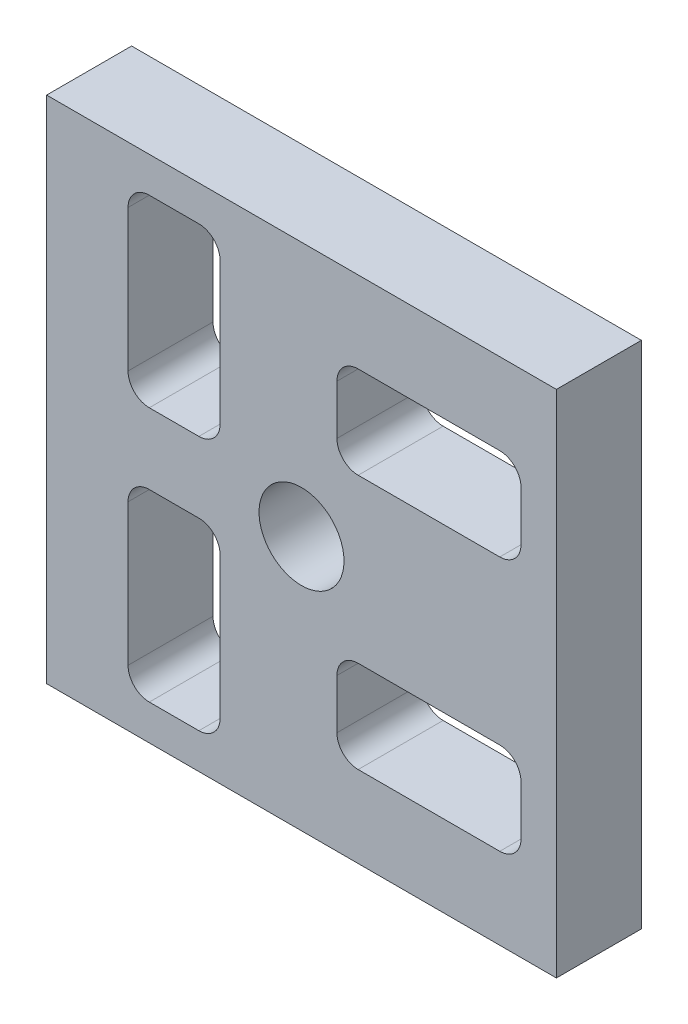
SolidWorks part; units mm, degrees
ref_plane "Alzado" through (0, 0, 0) normal (0, 0, 1) x (1, 0, 0)
ref_plane "Planta" through (0, 0, 0) normal (0, 1, 0) x (1, 0, 0)
ref_plane "Vista lateral" through (0, 0, 0) normal (1, 0, 0) x (0, 0, -1)
sketch "Model" plane through (0, 0, 0) normal (0, 0, 1) x (1, 0, 0)
  line L0 (208.8359, 161.3332) -> (208.8359, 179.3332)
  line L1 (190.8359, 179.3332) -> (190.8359, 161.3332)
  line L2 (201.8359, 176.4582) -> (206.8359, 176.4582)
  line L3 (207.5859, 175.7082) -> (207.5859, 173.9582)
  line L4 (206.8359, 173.2082) -> (201.8359, 173.2082)
  line L5 (201.0859, 173.9582) -> (201.0859, 175.7082)
  line L6 (201.8359, 167.4582) -> (206.8359, 167.4582)
  line L7 (207.5859, 166.7082) -> (207.5859, 164.9582)
  line L8 (206.8359, 164.2082) -> (201.8359, 164.2082)
  line L9 (201.0859, 164.9582) -> (201.0859, 166.7082)
  line L10 (196.9609, 168.3332) -> (196.9609, 163.3332)
  line L11 (196.2109, 162.5832) -> (194.4609, 162.5832)
  line L12 (193.7109, 163.3332) -> (193.7109, 168.3332)
  line L13 (194.4609, 169.0832) -> (196.2109, 169.0832)
  line L14 (196.9609, 177.3332) -> (196.9609, 172.3332)
  line L15 (196.2109, 171.5832) -> (194.4609, 171.5832)
  line L16 (193.7109, 172.3332) -> (193.7109, 177.3332)
  line L17 (194.4609, 178.0832) -> (196.2109, 178.0832)
  line L18 (190.8359, 179.3332) -> (208.8359, 179.3332)
  line L19 (190.8359, 161.3332) -> (208.8359, 161.3332)
  arc A0 (207.5859, 175.7082) -> (206.8359, 176.4582) centre (206.8359, 175.7082) ccw
  arc A1 (206.8359, 173.2082) -> (207.5859, 173.9582) centre (206.8359, 173.9582) ccw
  arc A2 (201.0859, 173.9582) -> (201.8359, 173.2082) centre (201.8359, 173.9582) ccw
  arc A3 (201.8359, 176.4582) -> (201.0859, 175.7082) centre (201.8359, 175.7082) ccw
  arc A4 (207.5859, 166.7082) -> (206.8359, 167.4582) centre (206.8359, 166.7082) ccw
  arc A5 (206.8359, 164.2082) -> (207.5859, 164.9582) centre (206.8359, 164.9582) ccw
  arc A6 (201.0859, 164.9582) -> (201.8359, 164.2082) centre (201.8359, 164.9582) ccw
  arc A7 (201.8359, 167.4582) -> (201.0859, 166.7082) centre (201.8359, 166.7082) ccw
  arc A8 (196.2109, 162.5832) -> (196.9609, 163.3332) centre (196.2109, 163.3332) ccw
  arc A9 (193.7109, 163.3332) -> (194.4609, 162.5832) centre (194.4609, 163.3332) ccw
  arc A10 (194.4609, 169.0832) -> (193.7109, 168.3332) centre (194.4609, 168.3332) ccw
  arc A11 (196.9609, 168.3332) -> (196.2109, 169.0832) centre (196.2109, 168.3332) ccw
  arc A12 (196.2109, 171.5832) -> (196.9609, 172.3332) centre (196.2109, 172.3332) ccw
  arc A13 (193.7109, 172.3332) -> (194.4609, 171.5832) centre (194.4609, 172.3332) ccw
  arc A14 (194.4609, 178.0832) -> (193.7109, 177.3332) centre (194.4609, 177.3332) ccw
  arc A15 (196.9609, 177.3332) -> (196.2109, 178.0832) centre (196.2109, 177.3332) ccw
  circle A16 centre (199.8359, 170.3332) radius 1.5
extrude "Saliente-Extruir1" add sketch "Model" along normal blind 3
